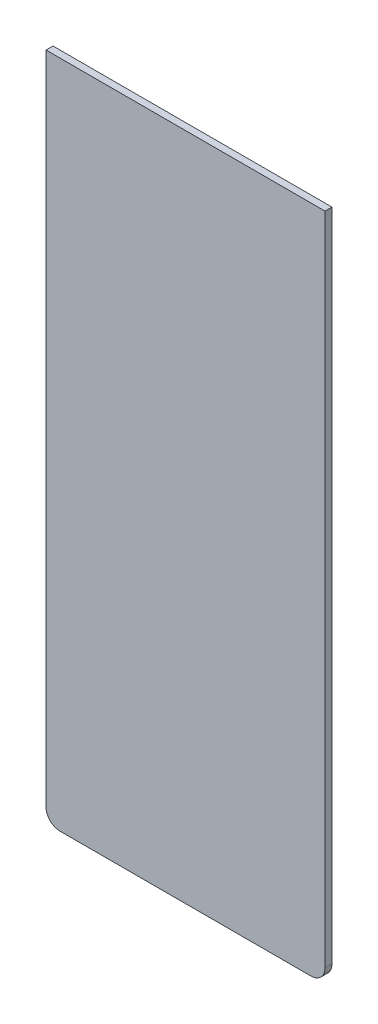
SolidWorks part; units mm, degrees
ref_plane "前视基准面" through (0, 0, 0) normal (0, 0, 1) x (1, 0, 0)
ref_plane "上视基准面" through (0, 0, 0) normal (0, 1, 0) x (1, 0, 0)
ref_plane "右视基准面" through (0, 0, 0) normal (1, 0, 0) x (0, 0, -1)
sketch "草图1" plane through (0, 0, 0) normal (0, 0, 1) x (1, 0, 0)
  line L1 (-100, -240) -> (100, -240)
  line L2 (-100, -240) -> (-100, 240)
  line L3 (-100, 240) -> (100, 240)
  line L4 (100, -240) -> (100, 240)
  line L5 (-100, -240) -> (100, 240) construction
  line L6 (-100, 240) -> (100, -240) construction
  point P0 (0, 0)
  dimension "D1" = 200
  dimension "D2" = 480
extrude "凸台-拉伸1" add sketch "草图1" along normal blind 5
fillet "圆角1" radius 10 2 edges at (-100, -240, 2.5) (100, -240, 2.5)
